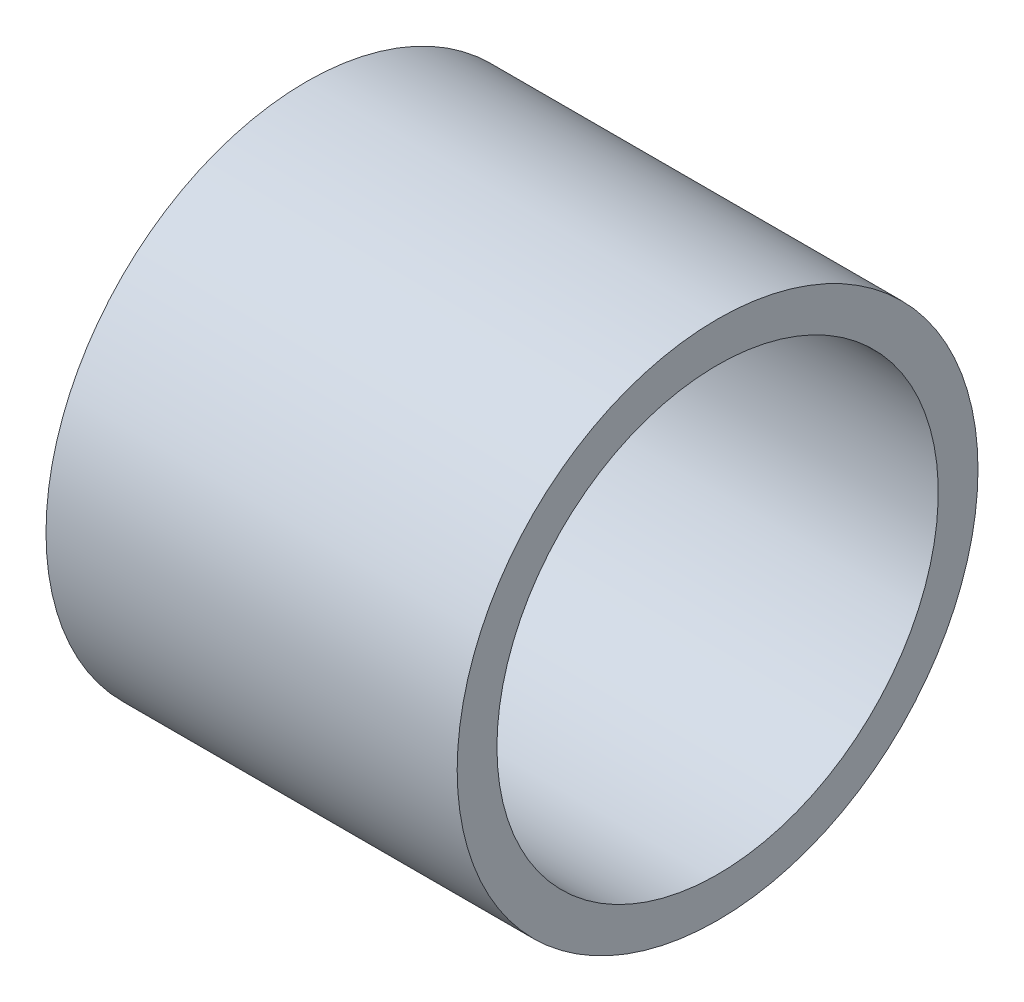
SolidWorks part; units mm, degrees
material "6061-T6 (SS)"
ref_plane "Front Plane" through (0, 0, 0) normal (0, 0, 1) x (1, 0, 0)
ref_plane "Top Plane" through (0, 0, 0) normal (0, 1, 0) x (1, 0, 0)
ref_plane "Right Plane" through (0, 0, 0) normal (1, 0, 0) x (0, 0, -1)
sketch "Sketch1" plane through (0, 0, 0) normal (1, 0, 0) x (0, 0, -1)
  circle A0 centre (0, 0) radius 24.13
  circle A1 centre (0, 0) radius 20.447
  dimension "D1" = 48.26
  dimension "D2" = 3.683
extrude "Boss-Extrude1" add sketch "Sketch1" along normal blind 38.1
